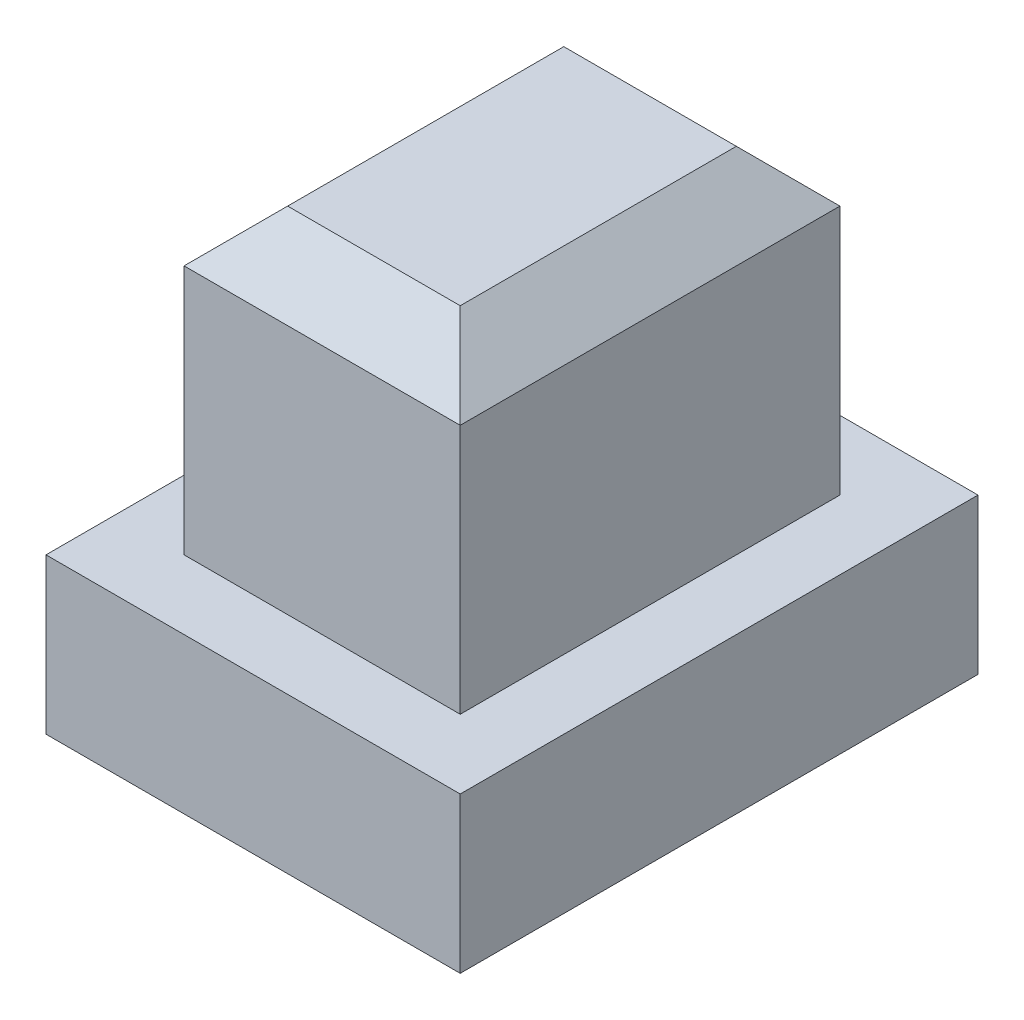
SolidWorks part; units mm, degrees
ref_plane "前视基准面" through (0, 0, 0) normal (0, 0, 1) x (1, 0, 0)
ref_plane "上视基准面" through (0, 0, 0) normal (0, 1, 0) x (1, 0, 0)
ref_plane "右视基准面" through (0, 0, 0) normal (1, 0, 0) x (0, 0, -1)
other "Configuration Table"
sketch "草图1" plane through (0, 0, 0) normal (0, 1, 0) x (1, 0, 0)
  line L1 (-0.2126, 4.0437) -> (4.5874, 4.0437)
  line L2 (-0.2126, 4.0437) -> (-0.2126, -1.9563)
  line L3 (-0.2126, -1.9563) -> (4.5874, -1.9563)
  line L4 (4.5874, 4.0437) -> (4.5874, -1.9563)
  dimension "D1" = 6
  dimension "D2" = 4.8
extrude "凸台-拉伸1" add sketch "草图1" along normal blind 1.8
sketch "草图2" plane through (0, 1.8, 0) normal (0, 1, 0) x (1, 0, 0)
  line L8 (0.5874, 3.2437) -> (0.5874, -1.1563)
  line L9 (0.5874, -1.1563) -> (3.7874, -1.1563)
  line L10 (3.7874, -1.1563) -> (3.7874, 3.2437)
  line L11 (3.7874, 3.2437) -> (0.5874, 3.2437)
  line L12 (0.5874, 3.2437) -> (0.5874, -1.1563)
  line L13 (0.5874, -1.1563) -> (3.7874, -1.1563)
  line L14 (3.7874, -1.1563) -> (3.7874, 3.2437)
  line L15 (3.7874, 3.2437) -> (0.5874, 3.2437)
  dimension "D1" = 0.8
extrude "凸台-拉伸2" add sketch "草图2" along normal blind 3.5
chamfer "倒角1" distance 0.6 angle 45 4 edges at (3.7874, 5.3, -1.0437) (2.1874, 5.3, 1.1563) (0.5874, 5.3, -1.0437) (2.1874, 5.3, -3.2437)
